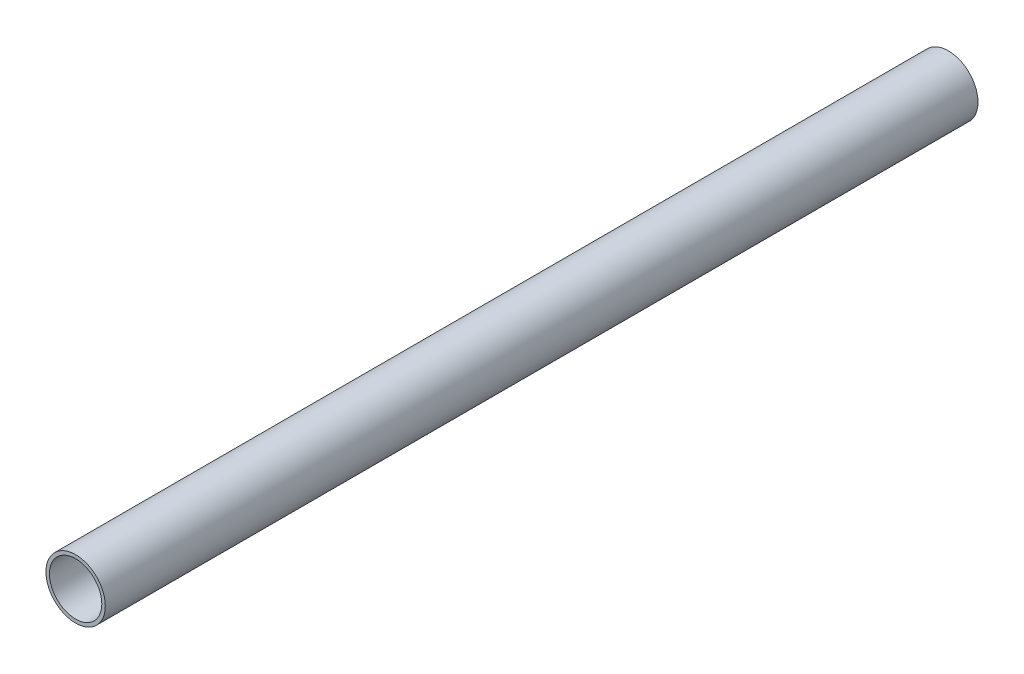
SolidWorks part; units mm, degrees
ref_plane "Front Plane" through (0, 0, 0) normal (0, 0, 1) x (1, 0, 0)
ref_plane "Top Plane" through (0, 0, 0) normal (0, 1, 0) x (1, 0, 0)
ref_plane "Right Plane" through (0, 0, 0) normal (1, 0, 0) x (0, 0, -1)
sketch "Sketch1" plane through (0, 0, 0) normal (0, 0, 1) x (1, 0, 0)
  circle A0 centre (0, 0) radius 15
  circle A1 centre (0, 0) radius 17
  dimension "D1" = 34
  dimension "D2" = 30
extrude "Boss-Extrude1" add sketch "Sketch1" along normal blind 500
